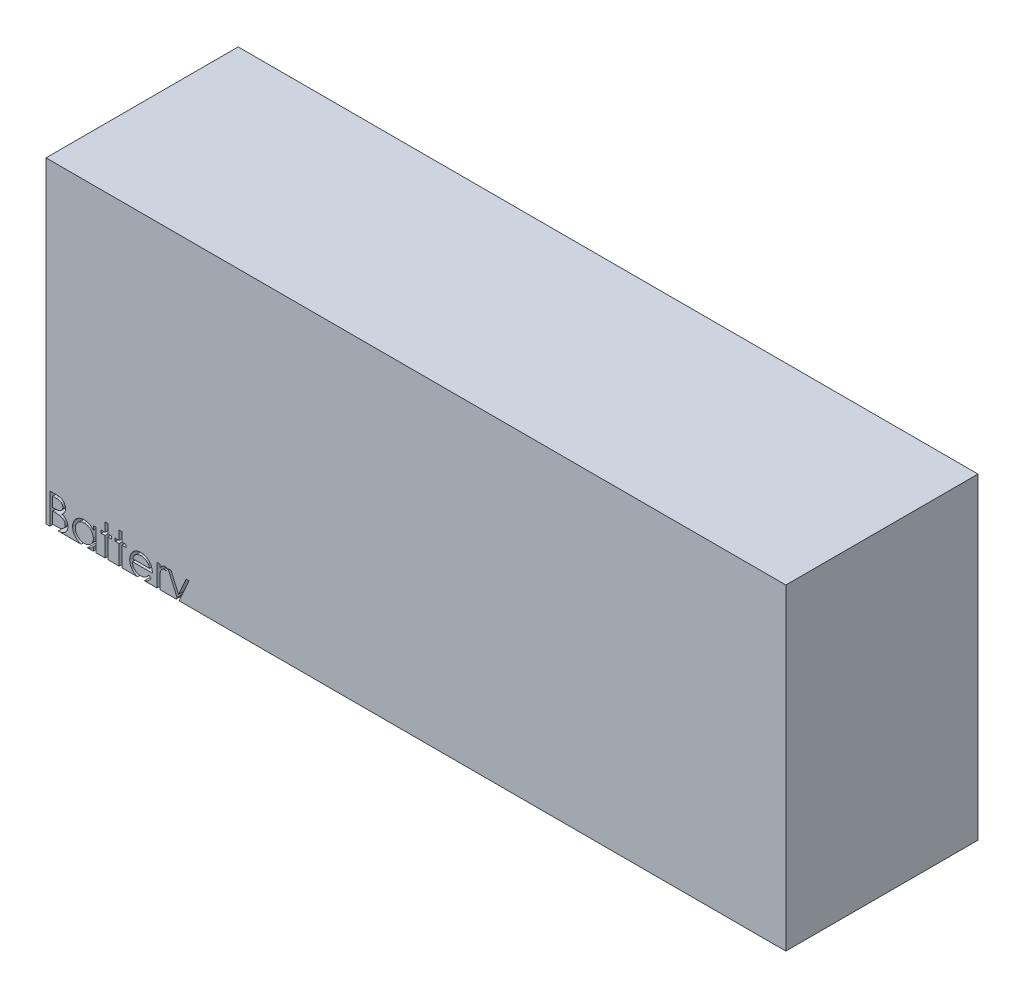
SolidWorks part; units mm, degrees
ref_plane "Front Plane" through (0, 0, 0) normal (0, 0, 1) x (1, 0, 0)
ref_plane "Top Plane" through (0, 0, 0) normal (0, 1, 0) x (1, 0, 0)
ref_plane "Right Plane" through (0, 0, 0) normal (1, 0, 0) x (0, 0, -1)
sketch "Sketch1" plane through (0, 0, 0) normal (0, 1, 0) x (1, 0, 0)
  line L1 (0, 0) -> (77, 0)
  line L2 (0, 0) -> (0, 20)
  line L3 (0, 20) -> (77, 20)
  line L4 (77, 0) -> (77, 20)
  dimension "D1" = 77
  dimension "D2" = 20
extrude "Boss-Extrude1" add sketch "Sketch1" along normal blind 33
sketch "Sketch2" plane through (0, 0, 0) normal (0, 0, 1) x (1, 0, 0)
  text T0 "Battery"
extrude "Cut-Extrude1" cut sketch "Sketch2" against normal blind 1.27
